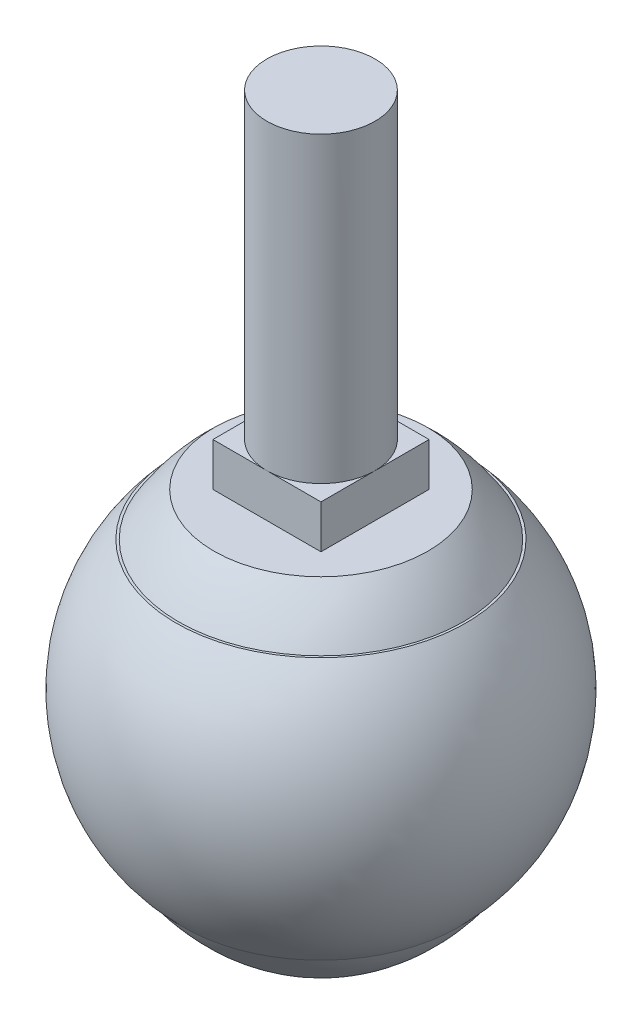
SolidWorks part; units mm, degrees
ref_plane "Front Plane" through (0, 0, 0) normal (0, 0, 1) x (1, 0, 0)
ref_plane "Top Plane" through (0, 0, 0) normal (0, 1, 0) x (1, 0, 0)
ref_plane "Right Plane" through (0, 0, 0) normal (1, 0, 0) x (0, 0, -1)
sketch "Sketch1" plane through (0, 0, 0) normal (0, 0, 1) x (1, 0, 0)
  line L0 (0, 8) -> (4.95, 8)
  line L1 (0, 8) -> (0, -10)
  line L2 (0, -10) -> (-49.4584, -10) construction
  ellipse E0 centre (0, 0) end of major axis (0, 10) minor radius 8.25 (0, -10) -> (4.95, 8) ccw
  dimension "D1" = 8.25
  dimension "D2" = 10
  dimension "D3" = 18
revolve "Revolve1" add sketch "Sketch1" angle 360 about L1
sketch "Sketch2" plane through (0, 8, 0) normal (0, 1, 0) x (1, 0, 0)
  line L1 (2.5, -2.5) -> (-2.5, -2.5)
  line L2 (2.5, -2.5) -> (2.5, 2.5)
  line L3 (2.5, 2.5) -> (-2.5, 2.5)
  line L4 (-2.5, -2.5) -> (-2.5, 2.5)
  line L5 (2.5, -2.5) -> (-2.5, 2.5) construction
  line L6 (2.5, 2.5) -> (-2.5, -2.5) construction
  point P0 (0, 0)
  dimension "D1" = 5
  dimension "D2" = 5
extrude "Boss-Extrude1" add sketch "Sketch2" along normal blind 2
sketch "Sketch3" plane through (0, 10, 0) normal (0, 1, 0) x (1, 0, 0)
  circle A0 centre (0, 0) radius 2.5
  dimension "D1" = 5
extrude "Boss-Extrude2" add sketch "Sketch3" along normal blind 14
sketch "Sketch4" plane through (0, 0, 0) normal (0, 0, 1) x (1, 0, 0)
  line L0 (-0.0015, 6) -> (6.7082, 6)
  line L1 (9.075, 0) -> (-9.075, 0) construction
  line L3 (-0.0015, 6) -> (-0.0015, -9)
  arc A0 (-0.0015, -9) -> (6.7082, 6) centre (0, 0) ccw
  dimension "D2" = 9
  dimension "D1" = 6
revolve "Revolve3" add sketch "Sketch4" angle 360 about L3
